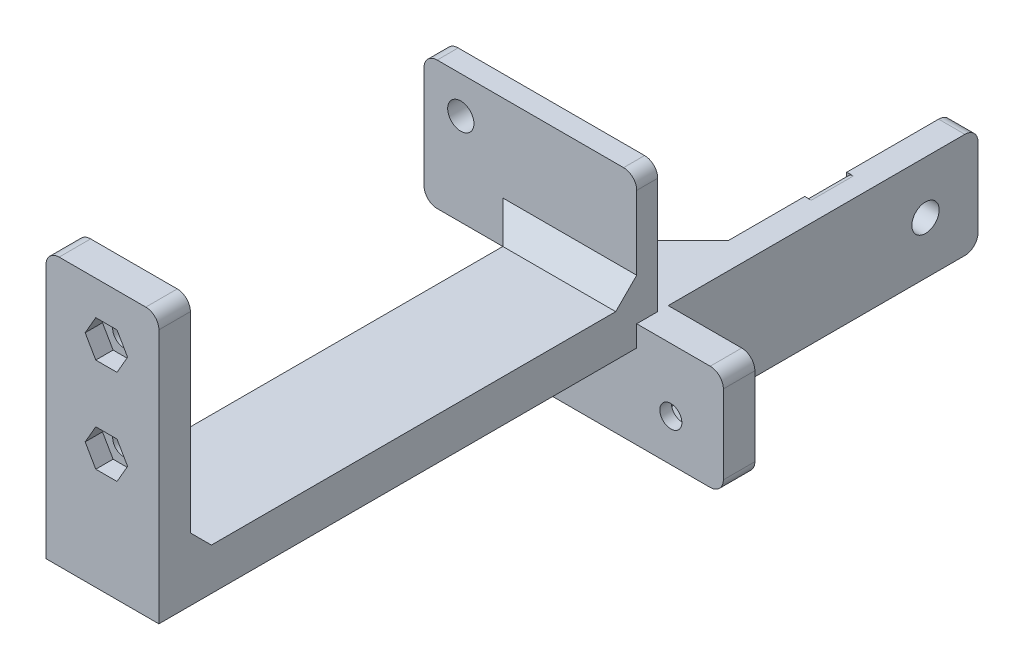
SolidWorks part; units mm, degrees
ref_plane "Спереди" through (0, 0, 0) normal (0, 0, 1) x (1, 0, 0)
ref_plane "Сверху" through (0, 0, 0) normal (0, 1, 0) x (1, 0, 0)
ref_plane "Справа" through (0, 0, 0) normal (1, 0, 0) x (0, 0, -1)
sketch "Эскиз3" plane through (0, 0, 0) normal (0, 0, 1) x (1, 0, 0)
  line L0 (-19, -10) -> (19, 10) construction
  line L1 (-19, 10) -> (19, 10)
  line L2 (-19, 10) -> (-19, -10)
  line L3 (-19, -10) -> (19, -10)
  line L4 (19, 10) -> (19, -10)
  point P4 (0, 0)
  dimension "D1" = 38
  dimension "D2" = 20
extrude "Бобышка-Вытянуть1" add sketch "Эскиз3" along normal blind 6
sketch "Эскиз4" plane through (-10.8, 0, 0) normal (0, 0, 1) x (1, 0, 0)
  line L11 (-8.2, -10) -> (29.8, -10) construction
  line L12 (8.3, -10) -> (13.3, -10)
  line L14 (8.3, -10) -> (8.3, 10)
  line L15 (8.3, 10) -> (13.3, 10)
  line L16 (13.3, -10) -> (13.3, 10)
  line L17 (29.8, 10) -> (-8.2, 10) construction
  line L18 (-8.2, 10) -> (-8.2, -10) construction
  point P12 (10.8, 10)
  point P13 (10.8, 10)
  dimension "D1" = 16.5
  dimension "D2" = 5
extrude "Бобышка-Вытянуть2" add sketch "Эскиз4" against normal blind 59
sketch "Эскиз9" plane through (0, 0, 6) normal (0, 0, 1) x (1, 0, 0)
  line L1 (2.5, 10) -> (-38, 10)
  line L2 (2.5, 10) -> (2.5, 34.5)
  line L3 (2.5, 34.5) -> (-38, 34.5)
  line L4 (-38, 10) -> (-38, 34.5)
  line L7 (19, 10) -> (-19, 10) construction
  dimension "D1" = 40.5
  dimension "D2" = 5
  dimension "D3" = 24.5
extrude "Бобышка-Вытянуть4" add sketch "Эскиз9" against normal blind 4
sketch "Эскиз12" plane through (0, 10, 0) normal (0, 1, 0) x (-1, 0, 0)
  line L0 (-2.5, 2) -> (-2.5, 6) construction
  line L1 (19, 6) -> (-2.5, 6)
  line L2 (19, 6) -> (19, 91)
  line L3 (19, 91) -> (-2.5, 91)
  line L4 (-2.5, 6) -> (-2.5, 91)
  line L5 (-19, 6) -> (-2.5, 6) construction
  dimension "D1" = 85
extrude "Бобышка-Вытянуть5" add sketch "Эскиз12" along normal mid plane 8
sketch "Эскиз13" plane through (0, 0, 91) normal (0, 0, 1) x (1, 0, 0)
  line L0 (2.5, 14) -> (-19, 14) construction
  line L1 (2.5, 6) -> (-19, 6)
  line L2 (2.5, 6) -> (2.5, 57)
  line L3 (2.5, 57) -> (-19, 57)
  line L4 (-19, 6) -> (-19, 57)
  dimension "D1" = 43
extrude "Бобышка-Вытянуть6" add sketch "Эскиз13" along normal blind 6
sketch "Эскиз23" plane through (0, 10, 0) normal (0, 1, 0) x (1, 0, 0)
  line L0 (-2.5, 16.5) -> (-19, 0)
  line L1 (-2.5, 59) -> (-2.5, 0) construction
  line L2 (-2.5, 0) -> (-19, 0) construction
  line L3 (-2.5, 16.5) -> (-2.5, 0)
  line L4 (-2.5, 0) -> (-19, 0)
  dimension "D1" = 45
extrude "Бобышка-Вытянуть8" add sketch "Эскиз23" against normal blind 4
sketch "Эскиз21" plane through (0, 0, -59) normal (0, 0, -1) x (-1, 0, 0)
  line L0 (2.5, 10) -> (2.5, -10) construction
  line L2 (1.25, 10) -> (2.5, 10)
  line L3 (2.5, 10) -> (2.5, 8.75)
  arc A0 (2.5, 8.75) -> (1.25, 10) centre (1.25, 8.75) ccw
  dimension "D1" = 2.5
extrude "Вырез-Вытянуть7" cut sketch "Эскиз21" against normal blind 8 from offset 20 offset against normal yes
sketch "Эскиз5" plane through (0, 0, 6) normal (0, 0, 1) x (1, 0, 0)
  line L0 (-9, -2) -> (9, -2) construction
  line L2 (19, 10) -> (2.5, 10) construction
  line L3 (2.5, 6) -> (-19, 6) construction
  circle A0 centre (-9, -2) radius 2.1
  circle A1 centre (9, -2) radius 2.1
  point P9 (0, -2)
  dimension "D1" = 4.2
  dimension "D2" = 4.2
  dimension "D3" = 18
  dimension "D4" = 12
  dimension "D5" = 8
extrude "Вырез-Вытянуть1" cut sketch "Эскиз5" against normal through all
sketch "Эскиз6" plane through (0, 0, 0) normal (0, 0, -1) x (-1, 0, 0)
  line L1 (-9, 2.1569) -> (-12.6, 0.0785)
  line L2 (-12.6, 0.0785) -> (-12.6, -4.0785)
  line L3 (-12.6, -4.0785) -> (-9, -6.1569)
  line L4 (-9, -6.1569) -> (-5.4, -4.0785)
  line L5 (-5.4, -4.0785) -> (-5.4, 0.0785)
  line L6 (-5.4, 0.0785) -> (-9, 2.1569)
  line L7 (9, 2.1569) -> (5.4, 0.0785)
  line L8 (5.4, 0.0785) -> (5.4, -4.0785)
  line L9 (5.4, -4.0785) -> (9, -6.1569)
  line L10 (9, -6.1569) -> (12.6, -4.0785)
  line L11 (12.6, -4.0785) -> (12.6, 0.0785)
  line L12 (12.6, 0.0785) -> (9, 2.1569)
  circle A0 centre (-9, -2) radius 3.6 construction
  circle A1 centre (9, -2) radius 3.6 construction
  dimension "D1" = 7.2
extrude "Вырез-Вытянуть2" cut sketch "Эскиз6" against normal blind 3.8
sketch "Эскиз7" plane through (2.5, 0, 0) normal (1, 0, 0) x (0, 0, -1)
  line L2 (59, 10) -> (59, -10) construction
  line L3 (59, -10) -> (0, -10) construction
  circle A0 centre (49, 0) radius 2.6
  dimension "D1" = 5.2
  dimension "D2" = 10
  dimension "D3" = 10
extrude "Вырез-Вытянуть3" cut sketch "Эскиз7" against normal through all
sketch "Эскиз17" plane through (0, 0, 91) normal (0, 0, -1) x (-1, 0, 0)
  line L0 (7.5, 29) -> (7.5, 47) construction
  line L1 (-2.5, 57) -> (19, 57) construction
  line L2 (-2.5, 14) -> (19, 14) construction
  line L3 (-2.5, 14) -> (-2.5, 57) construction
  circle A0 centre (7.5, 29) radius 2.1
  circle A1 centre (7.5, 47) radius 2.1
  dimension "D1" = 18
  dimension "D2" = 4.2
  dimension "D4" = 15
  dimension "D5" = 10
  dimension "D3" = 10
extrude "Вырез-Вытянуть4" cut sketch "Эскиз17" against normal through all
sketch "Эскиз18" plane through (0, 0, 97) normal (0, 0, 1) x (1, 0, 0)
  line L1 (-3.4585, 29) -> (-5.4793, 32.5)
  line L2 (-5.4793, 32.5) -> (-9.5207, 32.5)
  line L3 (-9.5207, 32.5) -> (-11.5415, 29)
  line L4 (-11.5415, 29) -> (-9.5207, 25.5)
  line L5 (-9.5207, 25.5) -> (-5.4793, 25.5)
  line L6 (-5.4793, 25.5) -> (-3.4585, 29)
  line L7 (-3.4585, 47) -> (-5.4793, 50.5)
  line L8 (-5.4793, 50.5) -> (-9.5207, 50.5)
  line L9 (-9.5207, 50.5) -> (-11.5415, 47)
  line L10 (-11.5415, 47) -> (-9.5207, 43.5)
  line L11 (-9.5207, 43.5) -> (-5.4793, 43.5)
  line L12 (-5.4793, 43.5) -> (-3.4585, 47)
  circle A0 centre (-7.5, 29) radius 3.5 construction
  circle A1 centre (-7.5, 47) radius 3.5 construction
  dimension "D1" = 7
extrude "Вырез-Вытянуть5" cut sketch "Эскиз18" against normal blind 3.3
sketch "Эскиз19" plane through (0, 0, 2) normal (0, 0, -1) x (-1, 0, 0)
  line L2 (38, 34.5) -> (38, 10) construction
  line L3 (-2.5, 34.5) -> (38, 34.5) construction
  circle A2 centre (31, 27.5) radius 2.5
  dimension "D4" = 7
  dimension "D5" = 7
extrude "Вырез-Вытянуть6" cut sketch "Эскиз19" against normal through all
fillet "Скругление2" radius 2.5 10 edges at (-19, 57, 94) (2.5, 57, 94) (19, 10, 3) (19, -10, 3) (-19, -10, 3) (-38, 34.5, 4) (-38, 10, 4) (2.5, 34.5, 4) (0, -10, -59) (0, 10, -59)
chamfer "Фаска2" distance 4 angle 45 3 edges at (-8.25, 14, 91) (-19, 12, 6) (-8.25, 14, 6)
sketch "Эскиз24" plane through (0, 0, 91) normal (0, 0, -1) x (-1, 0, 0)
  line L0 (7.5, 29) -> (7.5, 47) construction
